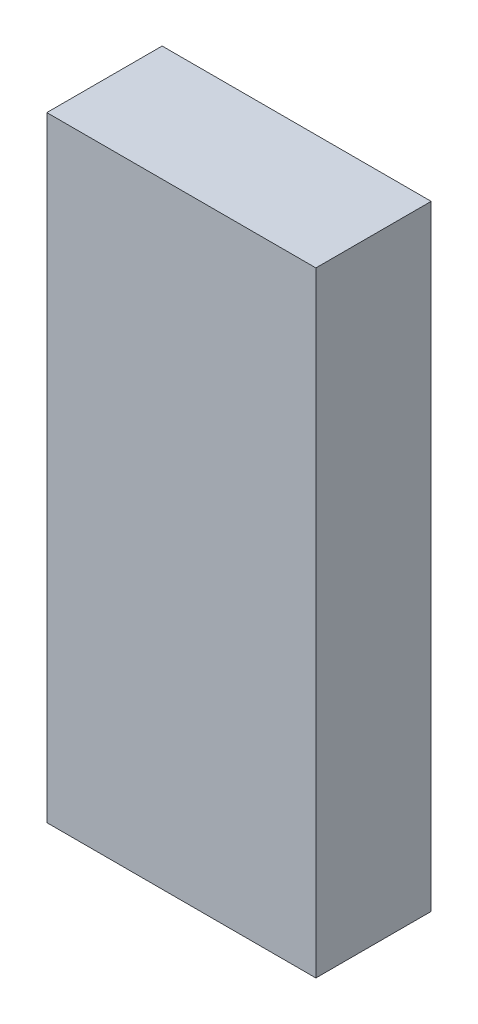
SolidWorks part; units mm, degrees
material "Pine"
ref_plane "Front Plane" through (0, 0, 0) normal (0, 0, 1) x (1, 0, 0)
ref_plane "Top Plane" through (0, 0, 0) normal (0, 1, 0) x (1, 0, 0)
ref_plane "Right Plane" through (0, 0, 0) normal (1, 0, 0) x (0, 0, -1)
sketch "Sketch1" plane through (0, 0, 0) normal (0, 1, 0) x (1, 0, 0)
  line L1 (0, 0) -> (88.9, 0)
  line L2 (0, 0) -> (0, 38.1)
  line L3 (0, 38.1) -> (88.9, 38.1)
  line L4 (88.9, 0) -> (88.9, 38.1)
  dimension "D1" = 38.1
  dimension "D2" = 88.9
extrude "Boss-Extrude1" add sketch "Sketch1" along normal blind 203.2
